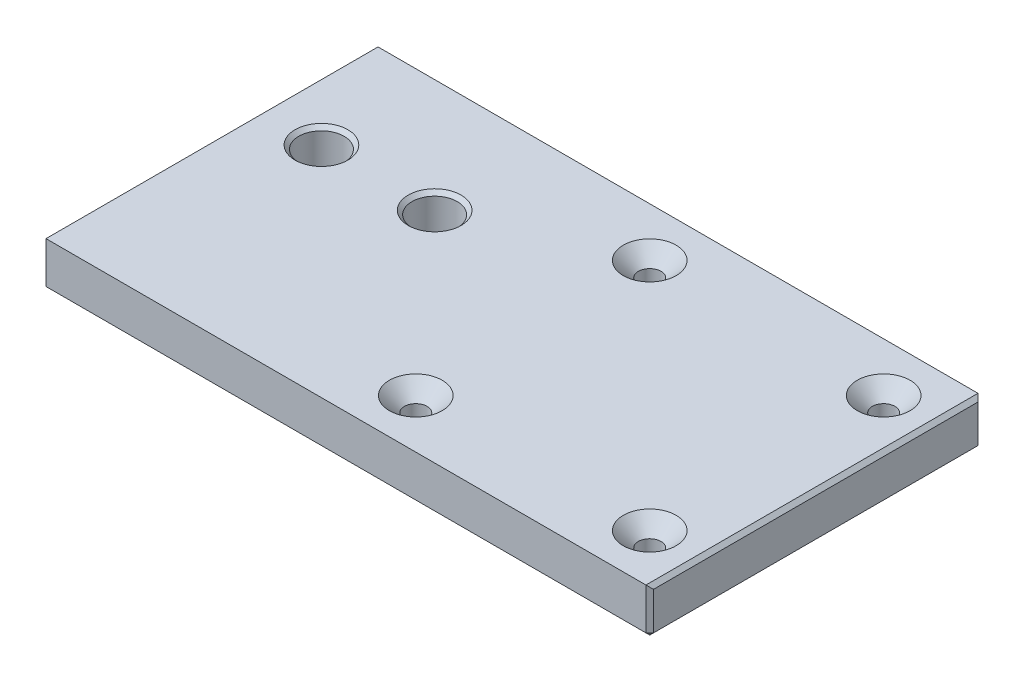
SolidWorks part; units mm, degrees
ref_plane "Alzado" through (0, 0, 0) normal (0, 0, 1) x (1, 0, 0)
ref_plane "Planta" through (0, 0, 0) normal (0, 1, 0) x (1, 0, 0)
ref_plane "Vista lateral" through (0, 0, 0) normal (1, 0, 0) x (0, 0, -1)
sketch "Croquis1" plane through (0, 0, 0) normal (0, 1, 0) x (1, 0, 0)
  line L1 (-32.7283, 20.7785) -> (47.7717, 20.7785)
  line L2 (-32.7283, 20.7785) -> (-32.7283, -23.2215)
  line L3 (-32.7283, -23.2215) -> (47.7717, -23.2215)
  line L4 (47.7717, 20.7785) -> (47.7717, -23.2215)
  circle A0 centre (10.2717, 14.2785) radius 1.5
  circle A1 centre (41.2717, 14.2785) radius 1.5
  circle A2 centre (10.2717, -16.7215) radius 1.5
  circle A3 centre (41.2717, -16.7215) radius 1.5
  circle A4 centre (-24.7283, 5.7785) radius 3
  circle A5 centre (-9.7283, 5.7785) radius 3
  dimension "D7" = 3
  dimension "D8" = 6
  dimension "D9" = 6
  dimension "D10" = 3
  dimension "D11" = 3
  dimension "D12" = 3
  dimension "D1" = 44
  dimension "D2" = 20
  dimension "D3" = 31
  dimension "D4" = 31
  dimension "D5" = 6.5
  dimension "D6" = 6.5
  dimension "D14" = 8
  dimension "D15" = 15
  dimension "D16" = 15
extrude "Saliente-Extruir1" add sketch "Croquis1" along normal blind 6
chamfer "Chaflán1" distance 0.5 angle 45 18 edges at (41.2717, 0, 18.2215) (41.2717, 0, -12.7785) (10.2717, 0, -12.7785) (10.2717, 0, 18.2215) (-32.7283, 3, -20.7785) (-32.7283, 3, 23.2215) (47.7717, 3, 23.2215) (7.5217, 0, 23.2215) (47.7717, 0, 1.2215) (-32.7283, 0, 1.2215) (7.5217, 0, -20.7785) (47.7717, 3, -20.7785) (47.7717, 6, 1.2215) (-32.7283, 6, 1.2215) (-9.7283, 0, -2.7785) (-24.7283, 0, -2.7785) (-9.7283, 6, -2.7785) (-24.7283, 6, -2.7785)
chamfer "Chaflán2" distance 2 angle 45 4 edges at (10.2717, 6, 18.2215) (10.2717, 6, -12.7785) (41.2717, 6, 18.2215) (41.2717, 6, -12.7785)
